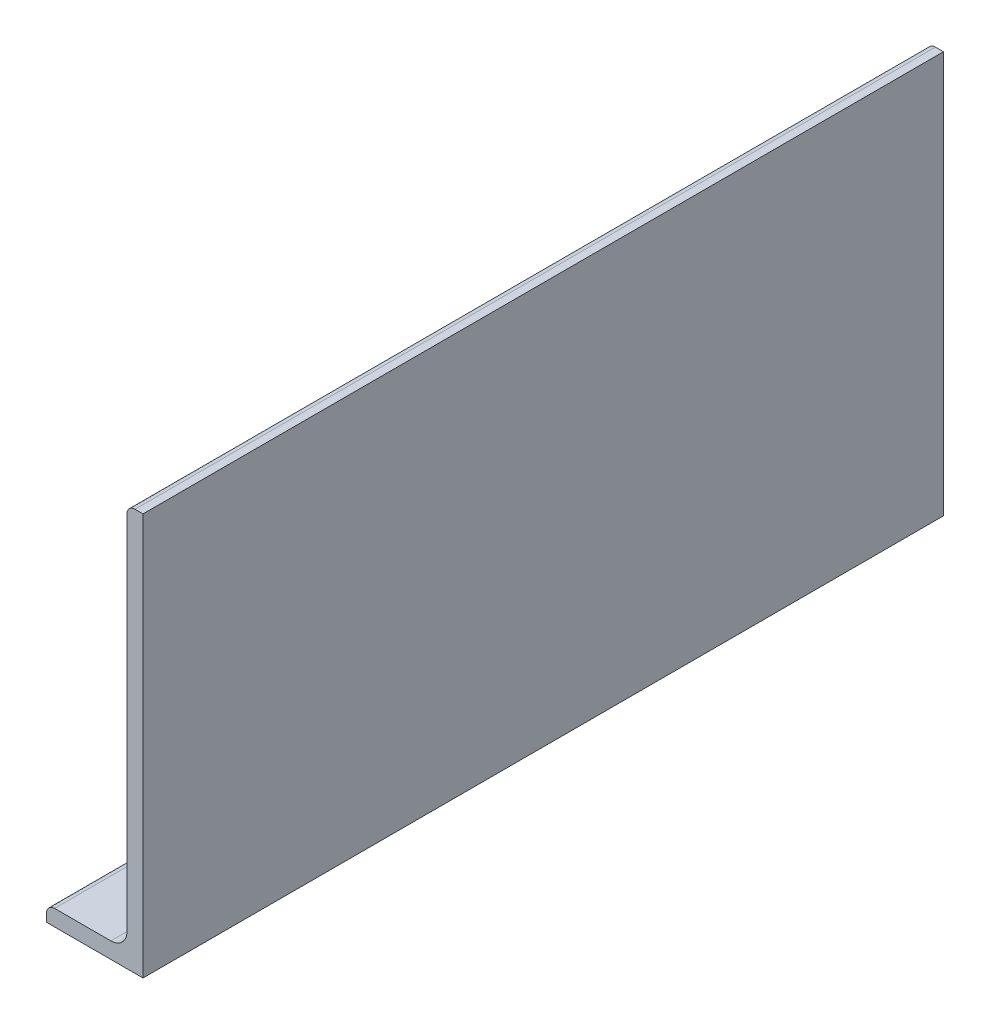
SolidWorks part; units mm, degrees
ref_plane "Front Plane" through (0, 0, 0) normal (0, 0, 1) x (1, 0, 0)
ref_plane "Top Plane" through (0, 0, 0) normal (0, 1, 0) x (1, 0, 0)
ref_plane "Right Plane" through (0, 0, 0) normal (1, 0, 0) x (0, 0, -1)
sketch "Sketch1" plane through (0, 0, 0) normal (0, 0, 1) x (1, 0, 0)
  line L0 (274.7296, -5.49) -> (274.7296, -55.49)
  line L1 (274.7296, -55.49) -> (262.7296, -55.49)
  line L2 (262.7296, -55.49) -> (262.7296, -53.49)
  line L3 (262.7296, -53.49) -> (272.7296, -53.49)
  line L4 (272.7296, -53.49) -> (272.7296, -5.49)
  line L5 (272.7296, -5.49) -> (274.7296, -5.49)
  dimension "D1" = 2
  dimension "D2" = 2
  dimension "D3" = 50
  dimension "D4" = 12
extrude "Boss-Extrude1" add sketch "Sketch1" along normal blind 99.58
fillet "Fillet1" radius 1 2 edges at (262.7296, -53.49, 49.79) (272.7296, -5.49, 49.79)
fillet "Fillet2" radius 2 1 edges at (272.7296, -53.49, 49.79)
sketch "Sketch2" plane through (0, -53.49, 0) normal (0, 1, 0) x (1, 0, 0)
  line L0 (270.7296, 0) -> (263.7296, 0) construction
  line L1 (262.7296, -99.58) -> (262.7296, 0) construction
  line L2 (270.7296, -99.58) -> (263.7296, -99.58) construction
  circle A0 centre (267.2296, -20) radius 1.6
  circle A1 centre (267.2296, -79.58) radius 1.6
  dimension "D1" = 3.2
  dimension "D2" = 3.2
  dimension "D3" = 20
  dimension "D4" = 4.5
  dimension "D5" = 20
  dimension "D6" = 4.5
extrude "Cut-Extrude1" cut sketch "Sketch2" against normal through all
